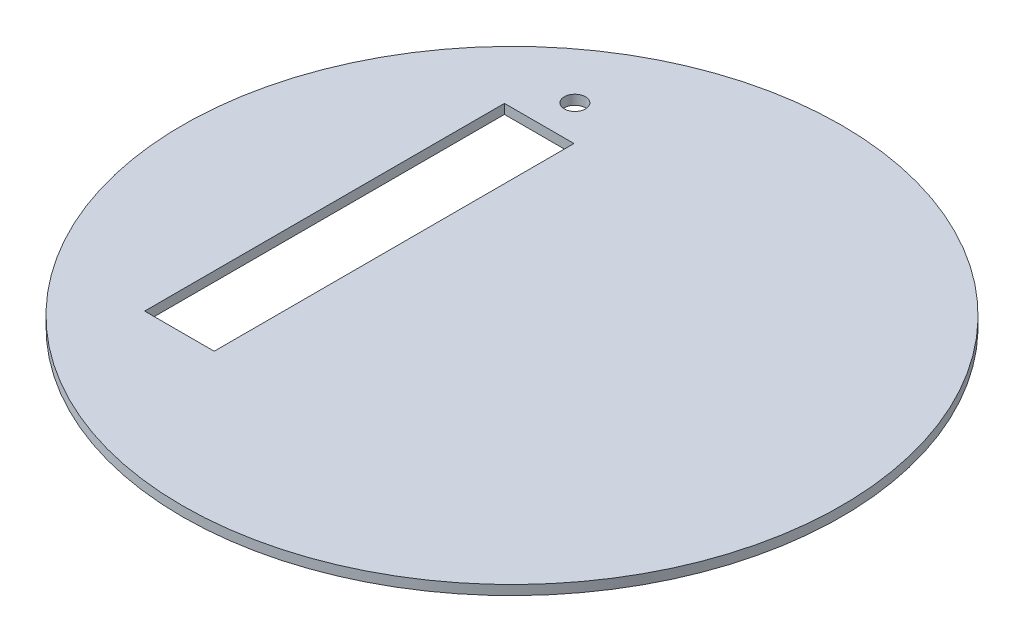
SolidWorks part; units mm, degrees
ref_plane "Front Plane" through (0, 0, 0) normal (0, 0, 1) x (1, 0, 0)
ref_plane "Top Plane" through (0, 0, 0) normal (0, 1, 0) x (1, 0, 0)
ref_plane "Right Plane" through (0, 0, 0) normal (1, 0, 0) x (0, 0, -1)
sketch "Sketch1" plane through (0, 0, 0) normal (0, 0, 1) x (1, 0, 0)
  line L0 (55, 0) -> (-55, 0) construction
  line L1 (0, 3.18) -> (0, 0)
  line L2 (0, 3.18) -> (109, 3.18)
  line L4 (109, 0) -> (0, 0)
  line L5 (109, 3.18) -> (109, 0)
  line L9 (0, 4.511) -> (0, 20.439) construction
  dimension "D1" = 109
  dimension "D4" = 3.18
revolve "Revolve1" add sketch "Sketch1" angle 360 about L9
sketch "Sketch2" plane through (0, 3.18, 0) normal (0, 1, 0) x (1, 0, 0)
  line L0 (-55, 0) -> (55, 0) construction
  line L1 (-39, -59.5) -> (-62, -59.5)
  line L2 (-39, -59.5) -> (-39, 59.5)
  line L3 (-39, 59.5) -> (-62, 59.5)
  line L4 (-62, -59.5) -> (-62, 59.5)
  line L5 (-39, -59.5) -> (-62, 59.5) construction
  line L6 (-39, 59.5) -> (-62, -59.5) construction
  line L7 (0, -55) -> (0, 55) construction
  line L8 (-50.5, 0) -> (-50.5, 85.0414) construction
  circle A0 centre (-50.5, 71.3022) radius 3.5
  point P0 (-50.5, 0)
  dimension "D4" = 7
  dimension "D1" = 39
  dimension "D2" = 23
  dimension "D3" = 119
extrude "Cut-Extrude1" cut sketch "Sketch2" against normal through all
